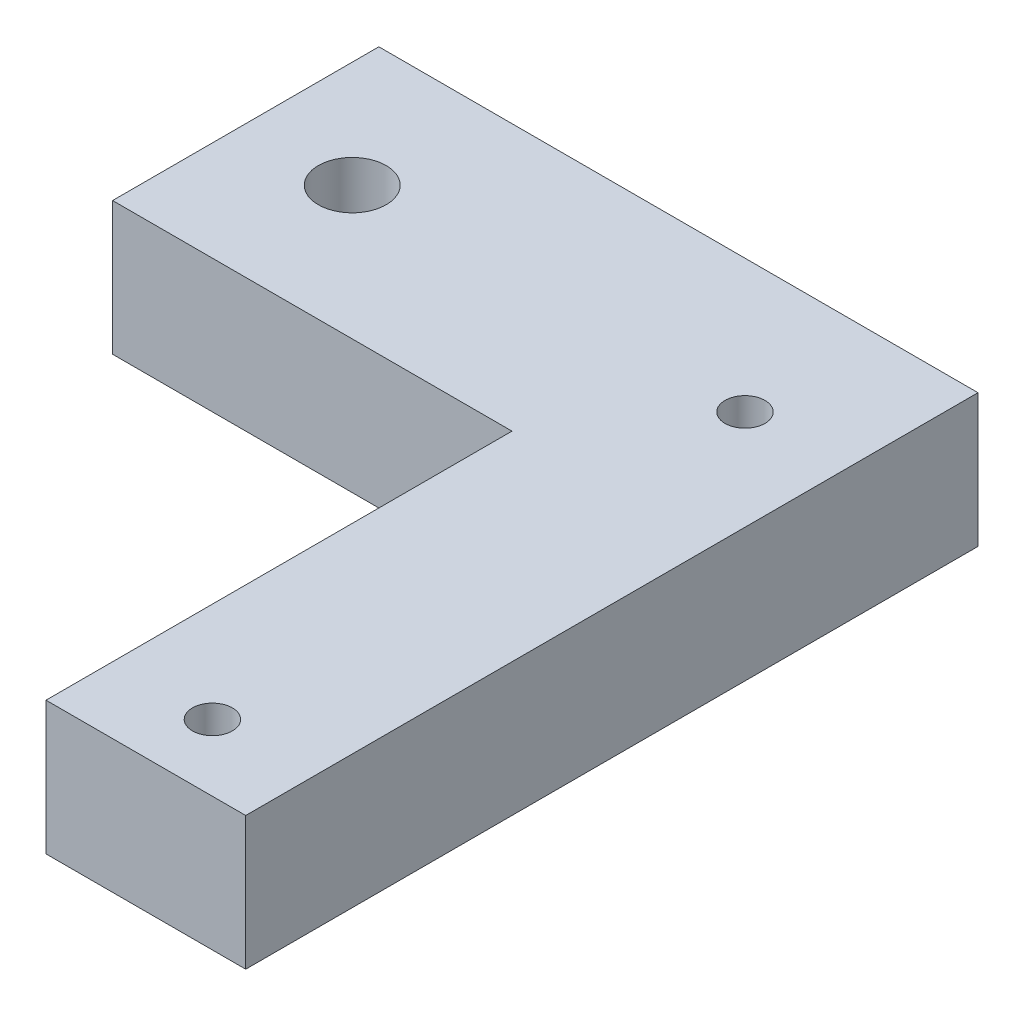
SolidWorks part; units mm, degrees
ref_plane "Front" through (0, 0, 0) normal (0, 0, 1) x (1, 0, 0)
ref_plane "Top" through (0, 0, 0) normal (0, 1, 0) x (1, 0, 0)
ref_plane "Right" through (0, 0, 0) normal (1, 0, 0) x (0, 0, -1)
sketch "Sketch1" plane through (0, 0, 0) normal (0, 1, 0) x (1, 0, 0)
  line L1 (-7.5, 27.5) -> (7.5, 27.5)
  line L2 (-7.5, 27.5) -> (-7.5, -27.5)
  line L3 (-7.5, -27.5) -> (7.5, -27.5)
  line L4 (7.5, 27.5) -> (7.5, -27.5)
  line L5 (-7.5, 27.5) -> (7.5, -27.5) construction
  line L6 (-7.5, -27.5) -> (7.5, 27.5) construction
  line L7 (-7.5, 27.5) -> (-37.5, 27.5)
  line L8 (-7.5, 27.5) -> (-7.5, 7.5)
  line L9 (-7.5, 7.5) -> (-37.5, 7.5)
  line L10 (-37.5, 27.5) -> (-37.5, 7.5)
  line L11 (-7.5, 27.5) -> (-37.5, 7.5) construction
  line L12 (-7.5, 7.5) -> (-37.5, 27.5) construction
  circle A0 centre (0, 17.5) radius 1.5
  circle A1 centre (0, -22.5) radius 1.5
  circle A3 centre (-29.5, 17.5) radius 2.55
  point P0 (0, 0)
  point P15 (-22.5, 17.5)
  dimension "D3" = 3
  dimension "D4" = 3
  dimension "D5" = 40
  dimension "D9" = 5.1
  dimension "D10" = 8
  dimension "D1" = 55
  dimension "D2" = 15
  dimension "D6" = 10
  dimension "D7" = 30
  dimension "D8" = 20
extrude "Boss-Extrude1" add sketch "Sketch1" along normal blind 10 contours L4 L1 L2 L3 A1 A0 | L7 L10 L9 L2 A3
